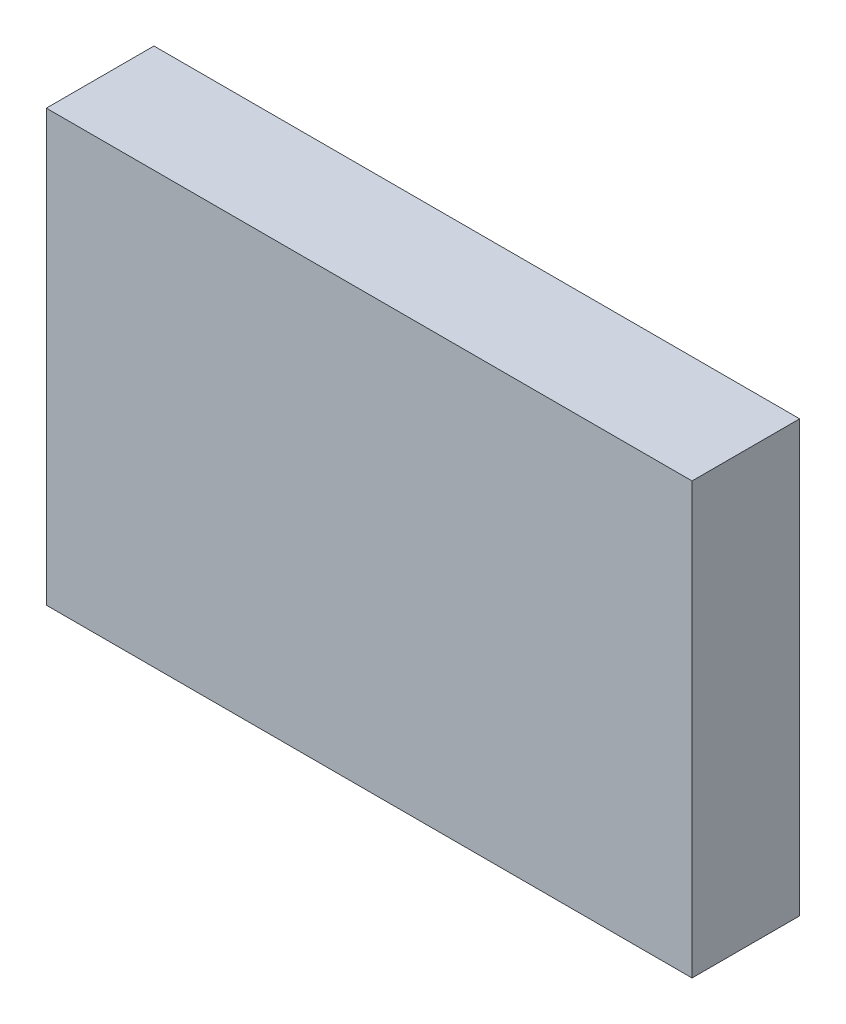
SolidWorks part; units mm, degrees
ref_plane "Ebene vorne" through (0, 0, 0) normal (0, 0, 1) x (1, 0, 0)
ref_plane "Ebene oben" through (0, 0, 0) normal (0, 1, 0) x (1, 0, 0)
ref_plane "Ebene rechts" through (0, 0, 0) normal (1, 0, 0) x (0, 0, -1)
sketch "Sketch1" plane through (0, 0, 0) normal (0, 0, 1) x (1, 0, 0)
  line L1 (0, 0) -> (30, 0)
  line L2 (0, 0) -> (0, 20)
  line L3 (0, 20) -> (30, 20)
  line L4 (30, 0) -> (30, 20)
  dimension "D1" = 20
  dimension "D2" = 30
extrude "Boss-Extrude1" add sketch "Sketch1" along normal blind 5
